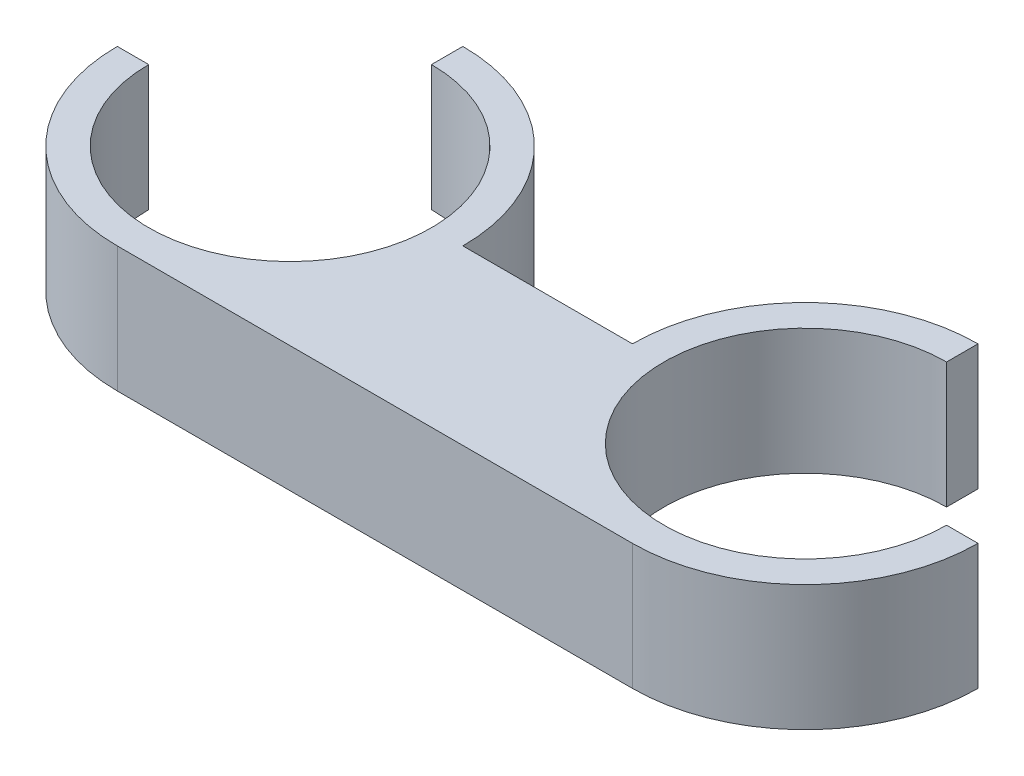
SolidWorks part; units mm, degrees
ref_plane "Front Plane" through (0, 0, 0) normal (0, 0, 1) x (1, 0, 0)
ref_plane "Top Plane" through (0, 0, 0) normal (0, 1, 0) x (1, 0, 0)
ref_plane "Right Plane" through (0, 0, 0) normal (1, 0, 0) x (0, 0, -1)
sketch "Sketch1" plane through (0, 0, 0) normal (0, 1, 0) x (1, 0, 0)
  line L0 (0, 11) -> (0, 9)
  line L5 (9, 0) -> (11, 0)
  line L6 (-11, 0) -> (-21.7952, 0)
  line L7 (-16.3976, 0) -> (-16.3976, -11)
  line L8 (-32.7952, -11) -> (0, -11)
  line L9 (-32.7952, 11) -> (-32.7952, 9)
  line L10 (-41.7952, 0) -> (-43.7952, 0)
  arc A0 (9, 0) -> (0, 9) centre (0, 0) cw
  arc A1 (11, 0) -> (0, 11) centre (0, 0) cw
  arc A2 (-41.7952, 0) -> (-32.7952, 9) centre (-32.7952, 0) ccw
  arc A3 (-43.7952, 0) -> (-32.7952, 11) centre (-32.7952, 0) ccw
  dimension "D1" = 9
  dimension "D2" = 2
extrude "Boss-Extrude1" add sketch "Sketch1" along normal blind 8 contours A3 L9 A2 L10 | A3 L8 L7 L6 | L8 A1 L6 L7 | A1 L5 A0 L0
